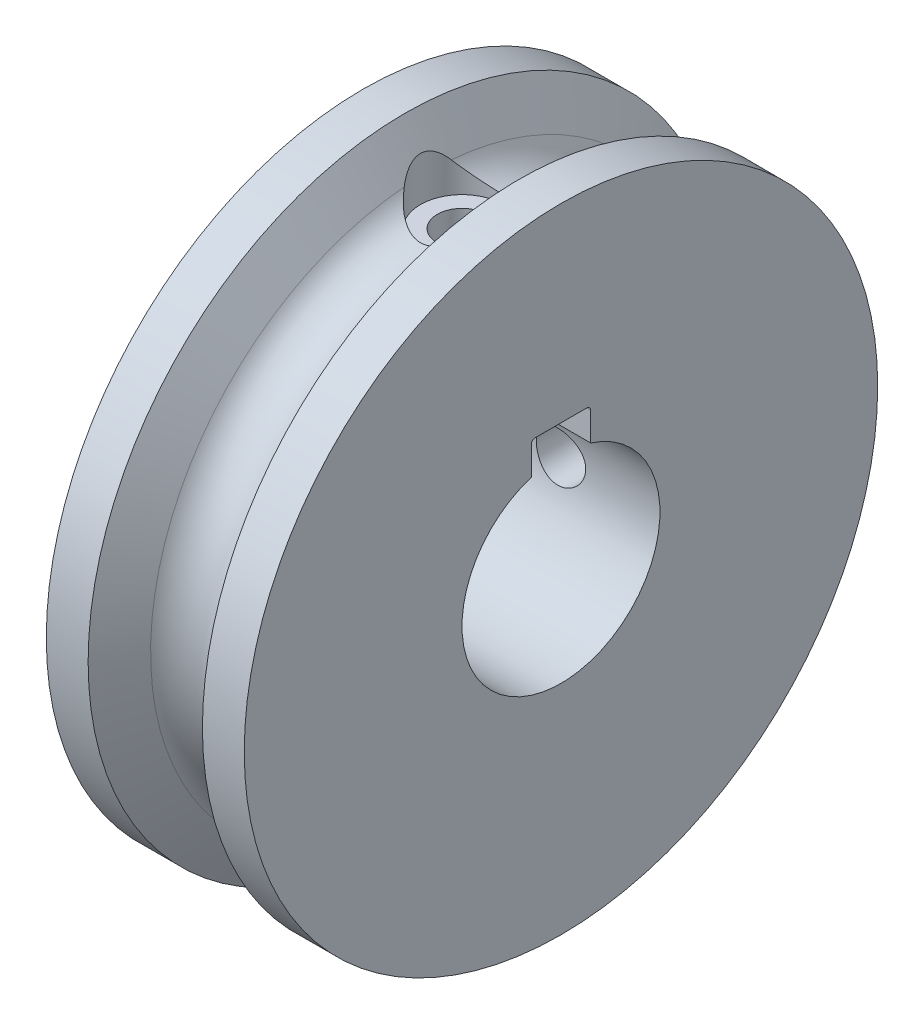
SolidWorks part; units mm, degrees
material "相當於S45C"
ref_plane "Front Plane" through (0, 0, 0) normal (0, 0, 1) x (1, 0, 0)
ref_plane "Top Plane" through (0, 0, 0) normal (0, 1, 0) x (1, 0, 0)
ref_plane "Right Plane" through (0, 0, 0) normal (1, 0, 0) x (0, 0, -1)
sketch "Sketch1" plane through (0, 0, 0) normal (0, 0, 1) x (1, 0, 0)
  line L0 (0, 5) -> (0, 16)
  line L5 (0, 16) -> (10, 16)
  line L6 (10, 16) -> (10, 5)
  line L7 (0, 0) -> (10, 0) construction
  line L8 (10, 5) -> (0, 5)
  line L9 (5, 16) -> (5, 0) construction
  dimension "T" = 10
  dimension "N" = 10
  dimension "D1." = 32
revolve "Revolve1" add sketch "Sketch1" angle 360 about L7
ref_plane "Plane1" through (0, 15, 0) normal (0, 1, 0) x (1, 0, 0)
sketch "Sketch2" plane through (0, 0, 0) normal (0, 0, 1) x (1, 0, 0)
  line L0 (5, 0) -> (5, 16) construction
  line L1 (10, -16) -> (10, 16) construction
  line L2 (0, 0) -> (10, 0) construction
  line L5 (0, 16) -> (0, -16) construction
  line L6 (5, 16) -> (7.1, 16)
  line L7 (5, 16) -> (5, 12.4)
  line L8 (5, 12.4) -> (7.1, 12.4)
  line L9 (7.1, 16) -> (7.1, 12.4)
  line L10 (0, 16) -> (10, 16) construction
  dimension "D1" = 12.4
  dimension "MSM_1" = 4.2
revolve "Cut-Revolve1" cut sketch "Sketch2" angle 360 about L9
hole_wizard "Tapped Hole1" positions "Sketch4" profile "Sketch3" tap size "M3x0.5" standard "JIS"
sketch "Sketch4" plane through (0, 15, 0) normal (0, 1, 0) x (1, 0, 0)
  line L0 (0, 0) -> (10, 0) construction
  line L1 (0, 16) -> (0, -16) construction
  line L3 (10, -16) -> (10, 16) construction
  point P0 (5, 0)
sketch "Sketch3" plane through (5, 15, 0) normal (1, 0, 0) x (0, 0, 1)
  line L0 (0, 0) -> (0, 31)
  line L1 (0, 31) -> (1.25, 31)
  line L2 (1.25, 31) -> (1.25, 0)
  line L5 (1.25, 0) -> (0, 0)
  line L11 (0, 0) -> (0, 31) construction
  dimension "Thru Tap Drill Dia." = 2.5
  dimension "Thru Tap Drill Depth" = 31
cosmetic thread "Hole Thread1" parameters "D1"=3
pattern_circular "CirPattern1" count 2 every 90 about axis through (0, 0, 0) along (-1, 0, 0) of "Cut-Revolve1", "Tapped Hole1"
pattern_circular "CirPattern2" [suppressed] count 2 every 90
sketch "Sketch5" plane through (0, 0, 0) normal (1, 0, 0) x (0, 0, -1)
  line L0 (0, 0) -> (0, 5) construction
  line L1 (-1.5, 0) -> (1.5, 0)
  line L2 (-1.5, 0) -> (-1.5, 6.2)
  line L3 (-1.3, 6.4) -> (1.3, 6.4)
  line L4 (1.5, 0) -> (1.5, 6.2)
  arc A1 (1.3, 6.4) -> (1.5, 6.2) centre (1.3, 6.2) cw
  arc A2 (-1.5, 6.2) -> (-1.3, 6.4) centre (-1.3, 6.2) cw
  circle A3 centre (0, 0) radius 5 construction
  dimension "D1" = 0.2
  dimension "B_s" = 3
  dimension "T_s" = 1.4
extrude "Cut-Extrude1" cut sketch "Sketch5" along normal through all
sketch "Sketch6" [suppressed] plane through (0, 0, 0) normal (0, 0, 1) x (1, 0, 0)
  line L0 (0, 0) -> (10, 0) construction
  line L1 (10, -23.5) -> (10, 23.5) construction
  line L2 (5, 0) -> (5, 23.5) construction
  line L4 (2.9358, 23.5) -> (3.9713, 21)
  line L5 (3.9713, 21) -> (6.0287, 21)
  line L6 (6.0287, 21) -> (7.0642, 23.5)
  line L7 (7.0642, 23.5) -> (2.9358, 23.5)
  line L8 (3.35, 22.5) -> (6.65, 22.5) construction
  line L11 (0, 23.5) -> (10, 23.5) construction
  dimension "D1" = 45
  dimension "W" = 4.4
  dimension "D2." = 26
  dimension "D3" = 1
  dimension "H_s" = 1.5
revolve "Cut-Revolve2" [suppressed] cut sketch "Sketch6" angle 360 about L0
sketch "Sketch7" plane through (0, 0, 0) normal (0, 0, 1) x (1, 0, 0)
  line L0 (0, 0) -> (10, 0) construction
  line L1 (10, -16) -> (10, 16) construction
  line L2 (5, 0) -> (5, 16) construction
  line L3 (0, 16) -> (10, 16) construction
  line L4 (2.1132, 16) -> (3.2679, 14)
  line L5 (7.8868, 16) -> (6.7321, 14)
  line L6 (2.1132, 16) -> (7.8868, 16)
  line L7 (0, 15) -> (10, 15) construction
  line L8 (10, 16) -> (10, 5) construction
  line L9 (0, 5) -> (0, 16) construction
  arc A0 (3.2679, 14) -> (6.7321, 14) centre (5, 15) ccw
  point P10 (5, 13)
  dimension "D1" = 60
  dimension "R" = 2
  dimension "D2." = 26
  dimension "H_s" = 2
revolve "Cut-Revolve3" cut sketch "Sketch7" angle 360 about L7
sketch "Sketch8" [suppressed] plane through (0, 0, 0) normal (0, 0, 1) x (1, 0, 0)
  line L0 (0, 0) -> (10, 0) construction
  line L1 (10, -23.5) -> (10, 23.5) construction
  line L2 (0, 5) -> (0, 23.5) construction
  line L3 (0, 23.5) -> (10, 23.5) construction
  line L4 (0, 22.5) -> (10, 22.5) construction
  line L7 (0, 23.5) -> (10, 23.5)
  line L8 (0, 23.5) -> (0, 23.1)
  line L9 (0, 23.1) -> (10, 23.1)
  line L10 (10, 23.5) -> (10, 23.1)
  dimension "DC" = 46.2
  dimension "MSM_1" = 0.6
revolve "Cut-Revolve4" [suppressed] cut sketch "Sketch8" angle 360 about L0
equation "\"D1@Sketch2\" = ( \"N@Sketch1\" / 2 ) + \"T_s@Sketch5\" + 6"
equation "\"Plane dim\"= \"P.D.\" * 0.5"
equation "\"Belt Radius\"= 1.5"
equation "\"Cut-Revolve1\"= if ( ( \"D1.@Sketch1\" - \"N@Sketch1\" ) / 2 - \"T_s@Sketch5\" > = 6 , \"unsuppressed\" , \"suppressed\" )"
equation "\"CirPattern1\" = if ( ( \"D1.@Sketch1\" - \"N@Sketch1\" ) / 2 - \"T_s@Sketch5\" > = 6 , \"unsuppressed\" , \"suppressed\" )"
equation "\"CirPattern2\" = if ( ( \"D1.@Sketch1\" - \"N@Sketch1\" ) / 2 - \"T_s@Sketch5\" > 6 , \"suppressed\" , \"unsuppressed\" )"
